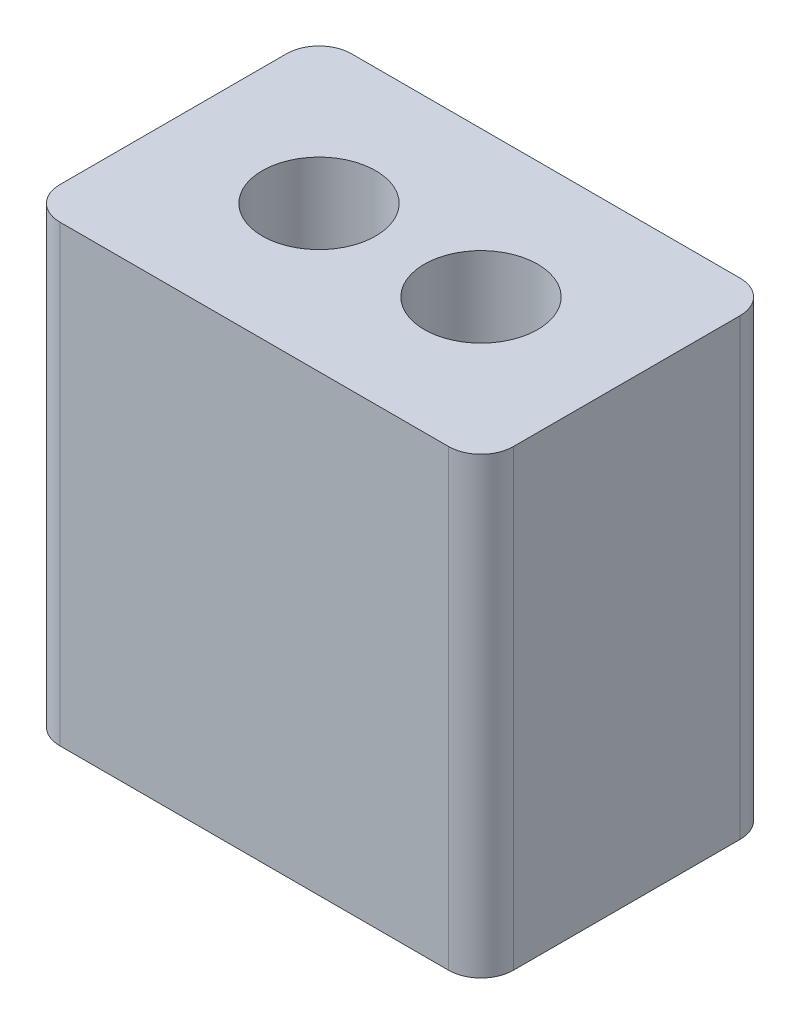
SolidWorks part; units mm, degrees
ref_plane "前视基准面" through (0, 0, 0) normal (0, 0, 1) x (1, 0, 0)
ref_plane "上视基准面" through (0, 0, 0) normal (0, 1, 0) x (1, 0, 0)
ref_plane "右视基准面" through (0, 0, 0) normal (1, 0, 0) x (0, 0, -1)
sketch "草图1" plane through (0, 0, 0) normal (0, 1, 0) x (1, 0, 0)
  line L0 (-7, 4.5) -> (7, -4.5) construction
  line L1 (-7, 4.5) -> (7, 4.5)
  line L2 (-7, 4.5) -> (-7, -4.5)
  line L3 (-7, -4.5) -> (7, -4.5)
  line L4 (7, 4.5) -> (7, -4.5)
  dimension "D1" = 9
  dimension "D2" = 14
extrude "凸台-拉伸1" add sketch "草图1" along normal blind 14
fillet "圆角1" radius 1 4 edges at (-7, 7, -4.5) (7, 7, -4.5) (7, 7, 4.5) (-7, 7, 4.5)
sketch "草图3" plane through (0, 14, 0) normal (0, 1, 0) x (1, 0, 0)
  line L0 (-2.5, 0) -> (2.5, 0) construction
  circle A0 centre (-2.5, 0) radius 1.75
  circle A1 centre (2.5, 0) radius 1.75
  point P2 (0, 0)
  dimension "D2" = 3.5
  dimension "D1" = 5
extrude "切除-拉伸2" cut sketch "草图3" against normal blind 7
sketch "草图4" plane through (0, 7, 0) normal (0, 1, 0) x (1, 0, 0)
  circle A0 centre (-2.5, 0) radius 0.95
  circle A1 centre (-2.5, 0) radius 1.75
  circle A2 centre (-2.5, 0) radius 1.75 construction
  circle A3 centre (2.5, 0) radius 1.75
  circle A4 centre (2.5, 0) radius 1.75 construction
  circle A5 centre (2.5, 0) radius 0.95
  dimension "D3" = 1.9
  dimension "D1" = 0
  dimension "D2" = 0
extrude "切除-拉伸3" cut sketch "草图4" against normal up to next
